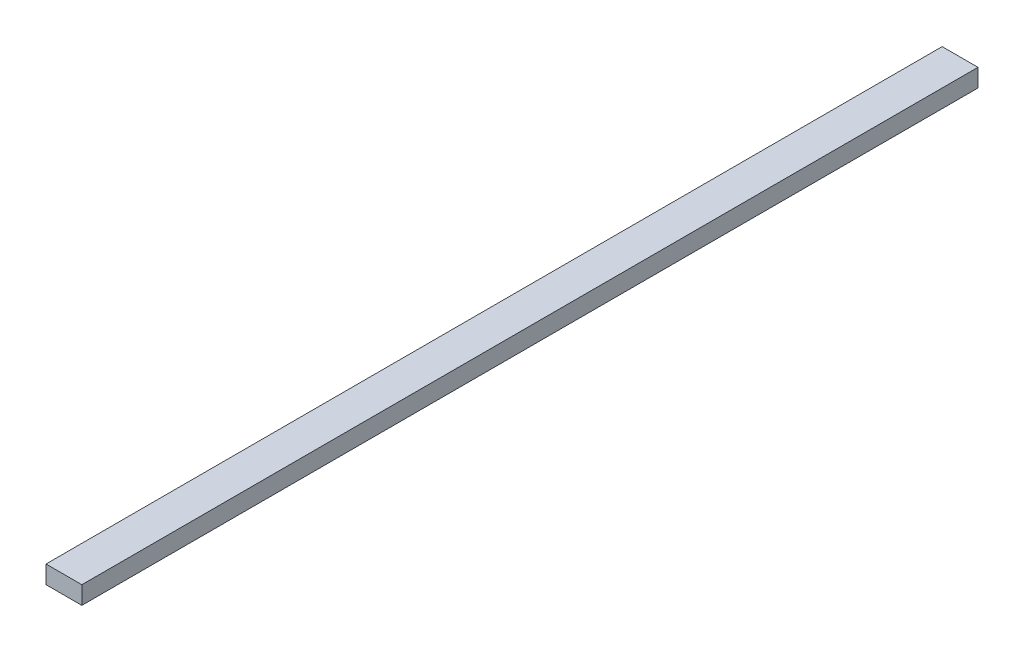
SolidWorks part; units mm, degrees
material "AISI 1020"
ref_plane "Front Plane" through (0, 0, 0) normal (0, 0, 1) x (1, 0, 0)
ref_plane "Top Plane" through (0, 0, 0) normal (0, 1, 0) x (1, 0, 0)
ref_plane "Right Plane" through (0, 0, 0) normal (1, 0, 0) x (0, 0, -1)
sketch "Sketch1" plane through (0, 0, 0) normal (0, 0, 1) x (1, 0, 0)
  line L1 (-10, 5) -> (10, 5)
  line L2 (-10, 5) -> (-10, -5)
  line L3 (-10, -5) -> (10, -5)
  line L4 (10, 5) -> (10, -5)
  line L5 (-10, 5) -> (10, -5) construction
  line L6 (-10, -5) -> (10, 5) construction
  point P0 (0, 0)
  dimension "D1" = 10
  dimension "D2" = 20
extrude "Boss-Extrude1" add sketch "Sketch1" along normal blind 500
